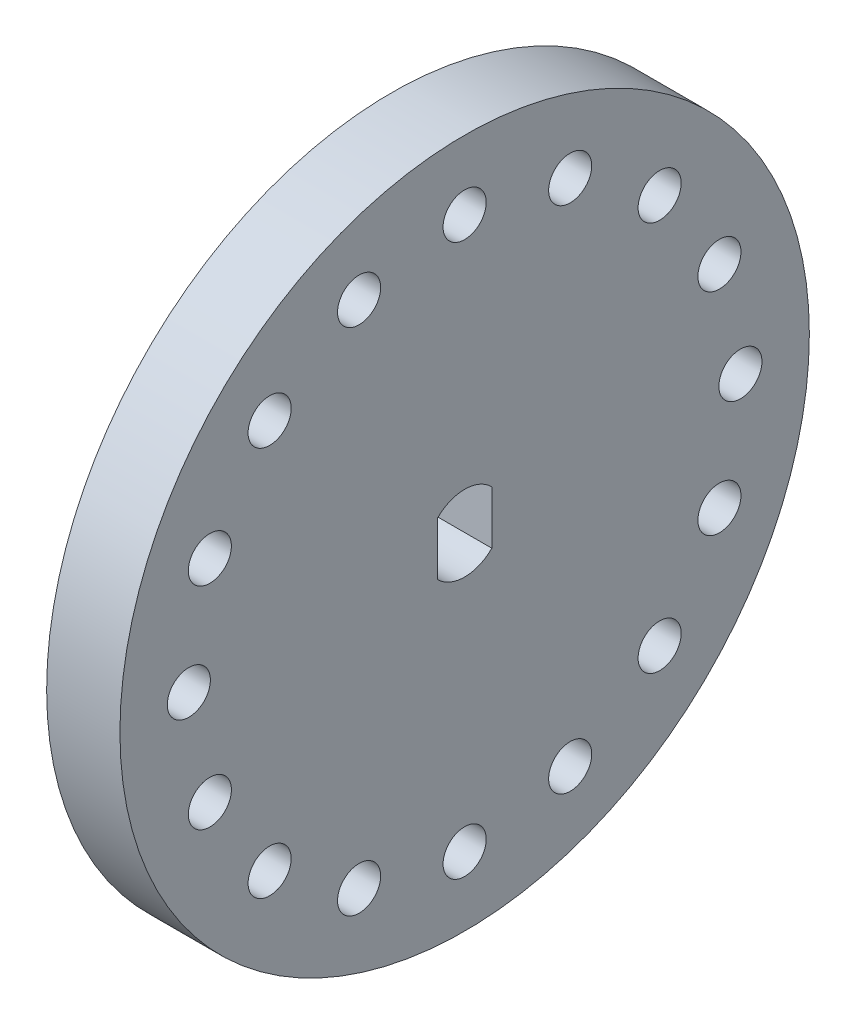
SolidWorks part; units mm, degrees
ref_plane "Front Plane" through (0, 0, 0) normal (0, 0, 1) x (1, 0, 0)
ref_plane "Top Plane" through (0, 0, 0) normal (0, 1, 0) x (1, 0, 0)
ref_plane "Right Plane" through (0, 0, 0) normal (1, 0, 0) x (0, 0, -1)
sketch "Sketch1" plane through (0, 0, 0) normal (1, 0, 0) x (0, 0, -1)
  line L0 (1, 0.9798) -> (1, -0.9798)
  line L1 (-1, 0.9798) -> (-1, -0.9798)
  line L2 (-1, 0) -> (1, 0) construction
  line L3 (0, 0) -> (0, 10.16) construction
  circle A0 centre (0, 0) radius 12.7
  arc A1 (1, 0.9798) -> (-1, 0.9798) centre (0, 0) ccw
  arc A2 (-1, -0.9798) -> (1, -0.9798) centre (0, 0) ccw
  circle A3 centre (0, 10.16) radius 0.7937
  circle A4 centre (3.8881, 9.3866) radius 0.7937
  circle A5 centre (7.1842, 7.1842) radius 0.7937
  circle A6 centre (9.3866, 3.8881) radius 0.7937
  circle A7 centre (10.16, 0) radius 0.7937
  circle A8 centre (9.3866, -3.8881) radius 0.7937
  circle A9 centre (7.1842, -7.1842) radius 0.7938
  circle A10 centre (3.8881, -9.3866) radius 0.7937
  circle A11 centre (0, -10.16) radius 0.7937
  circle A12 centre (-3.8881, -9.3866) radius 0.7937
  circle A13 centre (-7.1842, -7.1842) radius 0.7938
  circle A14 centre (-9.3866, -3.8881) radius 0.7938
  circle A15 centre (-10.16, 0) radius 0.7938
  circle A16 centre (-9.3866, 3.8881) radius 0.7938
  circle A17 centre (-7.1842, 7.1842) radius 0.7938
  circle A18 centre (-3.8881, 9.3866) radius 0.7938
  point P32 (0, 0)
  dimension "D1" = 25.4
  dimension "D2" = 2.8
  dimension "D4" = 1.5875
  dimension "D3" = 2
  dimension "D6" = 10.16
  dimension "D5" = 16
extrude "Base" add sketch "Sketch1" along normal blind 2.7
sketch "Sketch3" plane through (2.7, 0, 0) normal (1, 0, 0) x (0, 0, -1)
  circle A0 centre (0, 0) radius 10.16
